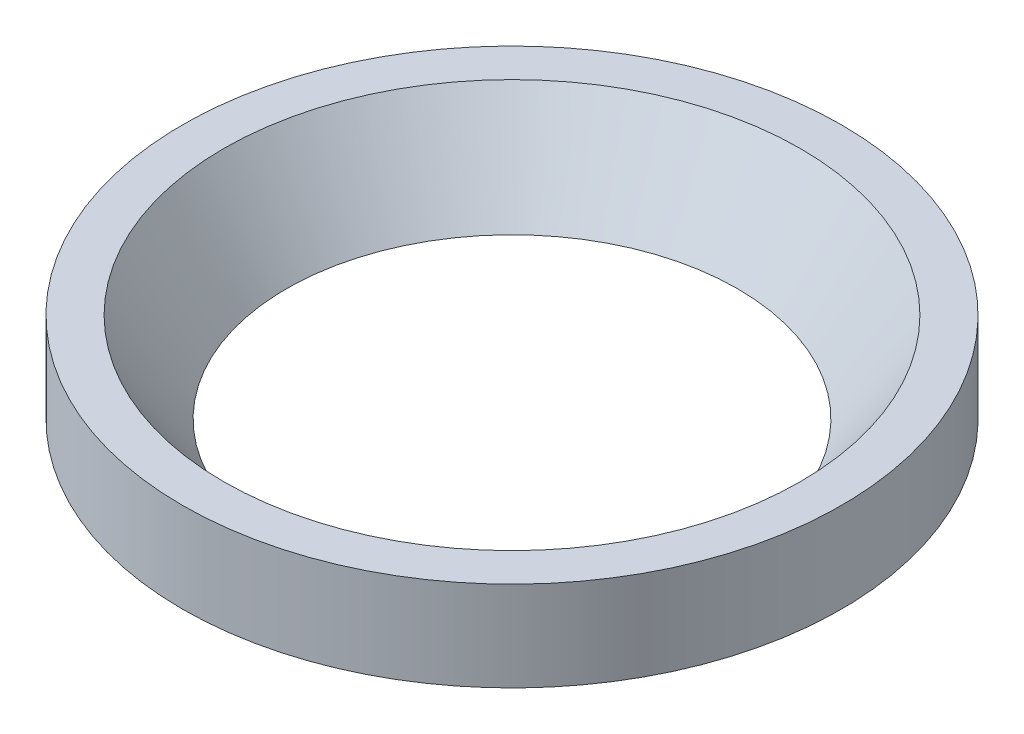
SolidWorks part; units mm, degrees
ref_plane "Front Plane" through (0, 0, 0) normal (0, 0, 1) x (1, 0, 0)
ref_plane "Top Plane" through (0, 0, 0) normal (0, 1, 0) x (1, 0, 0)
ref_plane "Right Plane" through (0, 0, 0) normal (1, 0, 0) x (0, 0, -1)
sketch "Sketch1" plane through (0, 0, 0) normal (0, 0, 1) x (1, 0, 0)
  line L0 (-19.939, 0) -> (19.939, 0) construction
  line L1 (19.939, 0) -> (61.1378, 58.838)
  line L2 (-19.939, 0) -> (-61.1378, 58.838)
  line L3 (-19.939, -109.3403) -> (-19.939, 58.838) construction
  line L4 (19.939, 58.838) -> (19.939, -109.3403) construction
  line L5 (19.939, 0) -> (43.18, -109.3403)
  line L6 (-19.939, 0) -> (-43.18, -109.3403)
  line L7 (0, 0) -> (0, -109.3403) construction
  line L8 (-43.18, -109.3403) -> (43.18, -109.3403) construction
  line L9 (-61.1378, 58.838) -> (61.1378, 58.838) construction
  line L10 (0, 0) -> (0, 58.838) construction
  line L11 (-69.85, 58.838) -> (69.85, 58.838) construction
  line L12 (-76.2, 58.838) -> (76.2, 58.838) construction
  line L13 (-61.1378, 58.838) -> (-69.85, 58.838)
  line L14 (-69.85, 58.838) -> (-69.85, 0)
  line L15 (-69.85, 0) -> (-76.2, 0)
  line L16 (-76.2, 0) -> (-76.2, -109.3403)
  line L17 (-76.2, -109.3403) -> (-43.18, -109.3403)
  line L18 (61.1378, 58.838) -> (69.85, 58.838)
  line L19 (69.85, 58.838) -> (69.85, 0)
  line L20 (69.85, 0) -> (76.2, 0)
  line L21 (76.2, 0) -> (76.2, -109.3403)
  line L22 (76.2, -109.3403) -> (43.18, -109.3403)
  line L23 (69.85, 39.788) -> (47.7988, 39.788)
  line L24 (-69.85, 39.788) -> (-47.7988, 39.788)
  line L25 (-76.2, 0) -> (76.2, 0) construction
  line L26 (-53.4699, 39.788) -> (-43.18, 0)
  line L27 (-43.18, 0) -> (-43.18, -76.2)
  line L28 (-43.18, -109.3403) -> (-43.18, -46.4417) construction
  line L29 (-43.18, -76.2) -> (-36.1358, -76.2)
  line L30 (-63.6778, 58.838) -> (63.6778, 58.838) construction
  line L31 (-69.85, 39.788) -> (-53.4699, 39.788) construction
  line L32 (-55.88, 0) -> (-49.53, -90.2903)
  line L33 (-63.1204, 39.788) -> (-63.1204, 35.0869) construction
  line L34 (-55.88, 0) -> (-63.1204, 39.788)
  line L35 (-43.18, -90.2903) -> (-62.0062, -90.2903) construction
  line L36 (-49.53, -90.2903) -> (-49.53, -109.3403)
  line L37 (43.18, -76.2) -> (36.1358, -76.2)
  line L38 (49.53, -90.2903) -> (49.53, -109.3403)
  line L39 (43.18, 0) -> (43.18, -76.2)
  line L40 (55.88, 0) -> (49.53, -90.2903)
  line L41 (55.88, 0) -> (63.1204, 39.788)
  line L42 (53.4699, 39.788) -> (43.18, 0)
  point P4 (0, 0)
  point P9 (-19.939, -25.2512)
  point P12 (19.939, 0)
  point P16 (0, 0)
  point P20 (0, -109.3403)
  point P22 (0, 58.838)
  point P25 (0, 58.838)
  point P37 (0, 0)
  point P39 (0, 0)
  point P46 (0, 58.838)
  dimension "D1" = 39.878
  dimension "D2" = 35
  dimension "D3" = 35
  dimension "D4" = 122.2756
  dimension "D5" = 12
  dimension "D6" = 86.36
  dimension "D7" = 139.7
  dimension "D8" = 152.4
  dimension "D9" = 19.05
  dimension "D10" = 19.05
  dimension "D11" = 152.4
  dimension "D12" = 20.5
  dimension "D13" = 12.7
  dimension "D14" = 6.35
  dimension "D15" = 127.3556
  dimension "D16" = 76.2
  dimension "D17" = 19.05
  dimension "D18" = 6.7296
ref_axis "Axis1" through (0, -117.7492, 0) along (0, 1, 0)
revolve "Revolve1" add sketch "Sketch1" angle 360 about axis through (0, -117.7492, 0) along (0, 1, 0)
